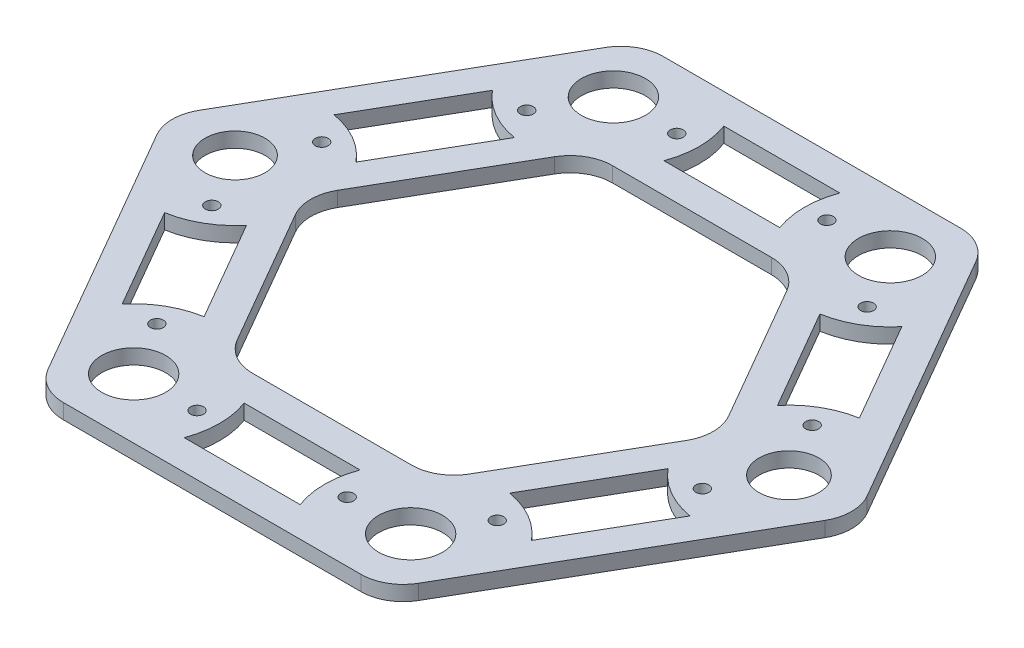
SolidWorks part; units mm, degrees
ref_plane "Front Plane" through (0, 0, 0) normal (0, 0, 1) x (1, 0, 0)
ref_plane "Top Plane" through (0, 0, 0) normal (0, 1, 0) x (1, 0, 0)
ref_plane "Right Plane" through (0, 0, 0) normal (1, 0, 0) x (0, 0, -1)
sketch "Sketch1" plane through (0, 0, 0) normal (0, 1, 0) x (1, 0, 0)
  line L0 (-46.9282, 108.3727) -> (-36.6617, 114.3) construction
  line L1 (141.4758, 8.9568) -> (78.4947, 118.0432)
  line L2 (62.9811, 127) -> (-62.9811, 127)
  line L3 (-78.4947, 118.0432) -> (-141.4758, 8.9568)
  line L4 (-141.4758, -8.9568) -> (-78.4947, -118.0432)
  line L5 (-62.9811, -127) -> (62.9811, -127)
  line L6 (78.4947, -118.0432) -> (141.4758, -8.9568)
  line L7 (0, 127) -> (-109.9852, 63.5) construction
  line L8 (-109.9852, 63.5) -> (-109.9852, -63.5) construction
  line L9 (-109.9852, -63.5) -> (0, -127) construction
  line L10 (73.3235, 127) -> (0, 0) construction
  line L11 (0, -55) -> (0, 55) construction
  line L12 (82.817, 8.9568) -> (49.1653, 67.2432)
  line L13 (33.6517, 76.2) -> (-33.6517, 76.2)
  line L14 (-49.1653, 67.2432) -> (-82.817, 8.9568)
  line L15 (-82.817, -8.9568) -> (-49.1653, -67.2432)
  line L16 (-33.6517, -76.2) -> (33.6517, -76.2)
  line L17 (49.1653, -67.2432) -> (82.817, -8.9568)
  line L18 (131.9823, 0) -> (65.9911, 114.3) construction
  line L19 (65.9911, 114.3) -> (55.358, 114.3) construction
  line L20 (-65.9911, 114.3) -> (-131.9823, 0) construction
  line L21 (-131.9823, 0) -> (-65.9911, -114.3) construction
  line L23 (65.9911, -114.3) -> (131.9823, 0) construction
  line L24 (51.3264, 88.9) -> (36.6617, 88.9) construction
  line L25 (-51.3264, 88.9) -> (-102.6529, 0) construction
  line L26 (-102.6529, 0) -> (-51.3264, -88.9) construction
  line L28 (51.3264, -88.9) -> (102.6529, 0) construction
  line L29 (102.6529, 0) -> (51.3264, 88.9) construction
  line L30 (-73.3235, 127) -> (-43.9941, 76.2) construction
  line L31 (0, -127) -> (109.9852, -63.5) construction
  line L32 (109.9852, -63.5) -> (109.9852, 63.5) construction
  line L33 (109.9852, 63.5) -> (0, 127) construction
  line L34 (-36.6617, 114.3) -> (-65.9911, 114.3) construction
  line L35 (-55, 0) -> (55, 0) construction
  line L36 (-146.647, 0) -> (-87.9882, 0) construction
  line L37 (65.9911, 114.3) -> (-65.9911, 114.3) construction
  line L38 (-46.8506, 88.9) -> (-51.3264, 88.9) construction
  line L43 (-24.5554, 114.3) -> (24.5554, 114.3)
  line L44 (-24.5554, 88.9) -> (24.5554, 88.9)
  line L51 (87.9882, 0) -> (43.9941, 76.2) construction
  line L52 (43.9941, 76.2) -> (-43.9941, 76.2) construction
  line L53 (146.647, 0) -> (73.3235, 127) construction
  line L54 (73.3235, 127) -> (-73.3235, 127) construction
  line L55 (73.3235, -127) -> (146.647, 0) construction
  line L56 (43.9941, -76.2) -> (87.9882, 0) construction
  line L57 (-43.9941, -76.2) -> (43.9941, -76.2) construction
  line L58 (-73.3235, -127) -> (73.3235, -127) construction
  line L59 (-87.9882, 0) -> (-43.9941, -76.2) construction
  line L60 (-146.647, 0) -> (-73.3235, -127) construction
  line L61 (-43.9941, 76.2) -> (-87.9882, 0) construction
  line L62 (-73.3235, 127) -> (-146.647, 0) construction
  line L63 (-67.3295, 86.5819) -> (-76.8545, 70.0841) construction
  line L64 (58.6588, 101.6) -> (-58.6588, 101.6) construction
  line L65 (-58.6588, 101.6) -> (-117.3176, 0) construction
  line L66 (-117.3176, 0) -> (-58.6588, -101.6) construction
  line L67 (-58.6588, -101.6) -> (58.6588, -101.6) construction
  line L68 (58.6588, -101.6) -> (117.3176, 0) construction
  line L69 (117.3176, 0) -> (58.6588, 101.6) construction
  line L70 (-74.9495, 73.3837) -> (-76.8545, 70.0841) construction
  line L71 (51.3264, 88.9) -> (-51.3264, 88.9) construction
  line L72 (24.5554, 114.3) -> (-24.5554, 114.3) construction
  line L73 (24.5554, 88.9) -> (-24.5554, 88.9) construction
  line L74 (-109.9852, 63.5) -> (109.9852, -63.5) construction
  line L75 (-86.709, 78.4156) -> (-111.2644, 35.8844)
  line L76 (-64.712, 65.7156) -> (-89.2673, 23.1844)
  line L77 (-108.6469, 15.0181) -> (-99.1219, 31.5159) construction
  line L78 (-89.2673, -23.1844) -> (-64.712, -65.7156)
  line L79 (-111.2644, -35.8844) -> (-86.709, -78.4156)
  line L80 (-65.9911, -114.3) -> (65.9911, -114.3) construction
  line L81 (-65.9911, -114.3) -> (65.9911, -114.3) construction
  line L82 (-51.3264, -88.9) -> (51.3264, -88.9) construction
  line L83 (-51.3264, -88.9) -> (51.3264, -88.9) construction
  line L84 (-24.5554, -88.9) -> (24.5554, -88.9)
  line L85 (-24.5554, -114.3) -> (24.5554, -114.3)
  line L86 (89.2673, -23.1844) -> (64.712, -65.7156)
  line L87 (111.2644, -35.8844) -> (86.709, -78.4156)
  line L88 (64.712, 65.7156) -> (89.2673, 23.1844)
  line L89 (86.709, 78.4156) -> (111.2644, 35.8844)
  circle A0 centre (0, 0) radius 127 construction
  circle A1 centre (-58.6588, 101.6) radius 13.5453
  circle A3 centre (0, 0) radius 109.9852 construction
  circle A9 centre (-58.6588, -101.6) radius 13.5453
  circle A12 centre (58.6588, -101.6) radius 13.5453
  circle A17 centre (58.6588, 101.6) radius 13.5453
  circle A18 centre (-117.3176, 0) radius 12.7
  circle A23 centre (117.3176, 0) radius 12.7
  arc A38 (49.1653, 67.2432) -> (33.6517, 76.2) centre (33.6517, 58.2865) ccw
  arc A39 (78.4947, 118.0432) -> (62.9811, 127) centre (62.9811, 109.0865) ccw
  arc A40 (141.4758, 8.9568) -> (141.4758, -8.9568) centre (125.9622, 0) cw
  arc A41 (82.817, 8.9568) -> (82.817, -8.9568) centre (67.3034, 0) cw
  arc A42 (33.6517, -76.2) -> (49.1653, -67.2432) centre (33.6517, -58.2865) ccw
  arc A43 (62.9811, -127) -> (78.4947, -118.0432) centre (62.9811, -109.0865) ccw
  arc A44 (-49.1653, -67.2432) -> (-33.6517, -76.2) centre (-33.6517, -58.2865) ccw
  arc A45 (-78.4947, -118.0432) -> (-62.9811, -127) centre (-62.9811, -109.0865) ccw
  arc A46 (-82.817, 8.9568) -> (-82.817, -8.9568) centre (-67.3034, 0) ccw
  arc A47 (-141.4758, 8.9568) -> (-141.4758, -8.9568) centre (-125.9622, 0) ccw
  arc A48 (-33.6517, 76.2) -> (-49.1653, 67.2432) centre (-33.6517, 58.2865) ccw
  arc A49 (-62.9811, 127) -> (-78.4947, 118.0432) centre (-62.9811, 109.0865) ccw
  circle A51 centre (-58.6588, 101.6) radius 17.3414 construction
  circle A52 centre (-58.6588, 101.6) radius 36.3914 construction
  circle A53 centre (-72.092, 78.333) radius 2.75
  circle A54 centre (-72.092, 78.333) radius 5.715 construction
  circle A55 centre (-31.7924, 101.6) radius 2.75
  arc A56 (-86.709, 78.4156) -> (-64.712, 65.7156) centre (-58.6588, 101.6) ccw
  arc A57 (-24.5554, 114.3) -> (-24.5554, 88.9) centre (-58.6588, 101.6) cw
  circle A58 centre (58.6588, 101.6) radius 36.3914 construction
  arc A59 (24.5554, 88.9) -> (24.5554, 114.3) centre (58.6588, 101.6) cw
  circle A60 centre (117.3176, 0) radius 36.3914 construction
  circle A61 centre (31.7924, 101.6) radius 2.75
  circle A62 centre (72.092, 78.333) radius 2.75
  circle A63 centre (-117.3176, 0) radius 36.3914 construction
  circle A64 centre (-117.3176, 0) radius 17.3414 construction
  arc A65 (-111.2644, 35.8844) -> (-89.2673, 23.1844) centre (-117.3176, 0) cw
  circle A66 centre (-103.8844, 23.267) radius 2.75
  circle A67 centre (-103.8844, -23.267) radius 2.75
  arc A68 (-89.2673, -23.1844) -> (-111.2644, -35.8844) centre (-117.3176, 0) cw
  circle A69 centre (-58.6588, -101.6) radius 36.3914 construction
  circle A70 centre (-31.7924, -101.6) radius 2.75
  circle A71 centre (-72.092, -78.333) radius 2.75
  circle A72 centre (103.8844, -23.267) radius 2.75
  circle A73 centre (103.8844, 23.267) radius 2.75
  circle A74 centre (72.092, -78.333) radius 2.75
  circle A75 centre (31.7924, -101.6) radius 2.75
  arc A76 (-64.712, -65.7156) -> (-86.709, -78.4156) centre (-58.6588, -101.6) ccw
  circle A77 centre (58.6588, -101.6) radius 36.3914 construction
  arc A78 (-24.5554, -88.9) -> (-24.5554, -114.3) centre (-58.6588, -101.6) cw
  arc A79 (24.5554, -88.9) -> (24.5554, -114.3) centre (58.6588, -101.6) ccw
  arc A80 (64.712, -65.7156) -> (86.709, -78.4156) centre (58.6588, -101.6) cw
  arc A81 (89.2673, -23.1844) -> (111.2644, -35.8844) centre (117.3176, 0) ccw
  arc A82 (64.712, 65.7156) -> (86.709, 78.4156) centre (58.6588, 101.6) ccw
  arc A83 (111.2644, 35.8844) -> (89.2673, 23.1844) centre (117.3176, 0) ccw
  dimension "D6" = 27.0906
  dimension "D9" = 11.43
  dimension "D10" = 25.4
  dimension "D14" = 17.9135
  dimension "D15" = 5.5
  dimension "D16" = 3.7961
  dimension "D17" = 12.7
  dimension "D18" = 3.81
  dimension "D1" = 254
  dimension "D2" = 30
  dimension "D3" = 50.8
  dimension "D4" = 12.7
  dimension "D5" = 25.4
extrude "Boss-Extrude1" add sketch "Sketch1" along normal blind 6.35
